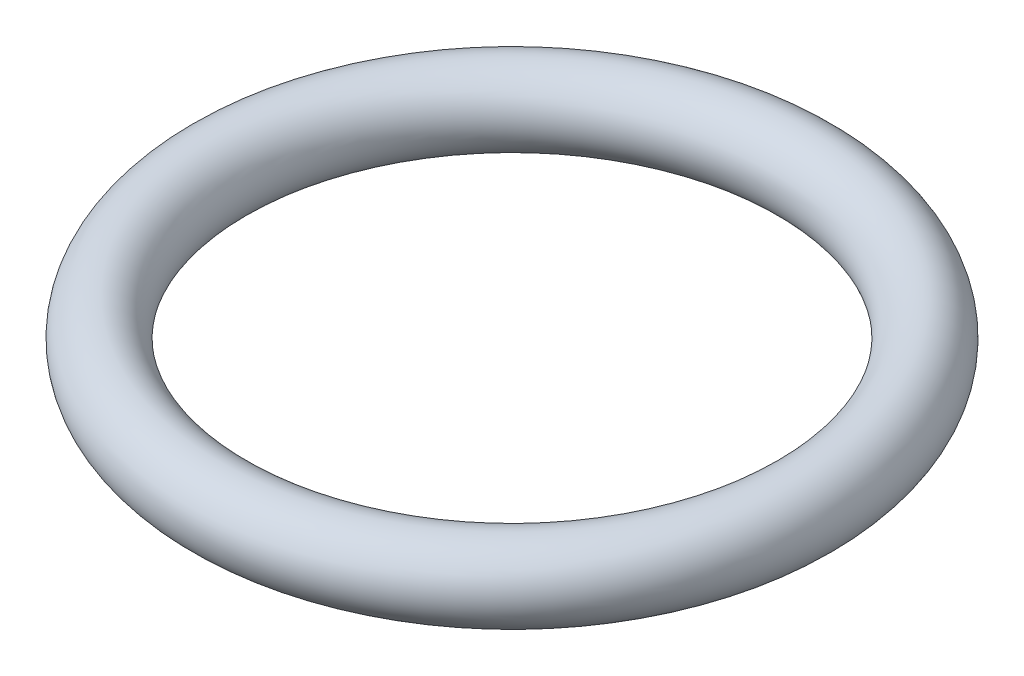
SolidWorks part; units mm, degrees
material "VITON"
ref_plane "Front Plane" through (0, 0, 0) normal (0, 0, 1) x (1, 0, 0)
ref_plane "Top Plane" through (0, 0, 0) normal (0, 1, 0) x (1, 0, 0)
ref_plane "Right Plane" through (0, 0, 0) normal (1, 0, 0) x (0, 0, -1)
sketch "MainBodyS" plane through (0, 0, 0) normal (0, 0, 1) x (1, 0, 0)
  line L0 (0, 0) -> (5.45, 0) construction
  line L1 (0, 0) -> (0, -1) construction
  circle A0 centre (5.45, 0) radius 0.7
  point P3 (6.15, 0)
  point P6 (-6.15, 0)
  point P7 (-4.75, 0)
  point P8 (4.75, 0)
  dimension "D1" = 1.4
  dimension "D2" = 1
  dimension "D3" = 10.9
  dimension "D4" = 12.3
  dimension "D5" = 9.5
revolve "MAIN BODY" add sketch "MainBodyS" angle 360 about L1
